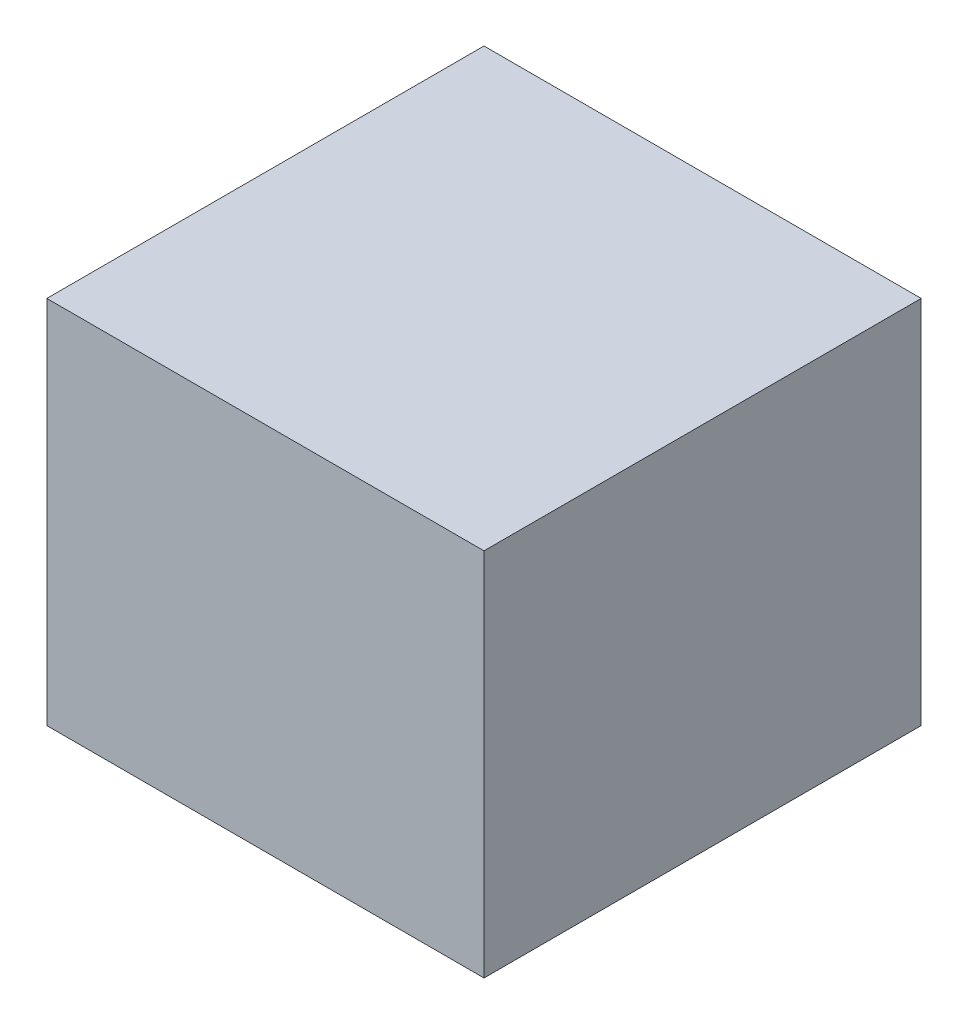
SolidWorks part; units mm, degrees
ref_plane "Front Plane" through (0, 0, 0) normal (0, 0, 1) x (1, 0, 0)
ref_plane "Top Plane" through (0, 0, 0) normal (0, 1, 0) x (1, 0, 0)
ref_plane "Right Plane" through (0, 0, 0) normal (1, 0, 0) x (0, 0, -1)
sketch "Sketch1" plane through (0, 0, 0) normal (0, 1, 0) x (1, 0, 0)
  line L1 (-165.1, -165.1) -> (165.1, -165.1)
  line L2 (-165.1, -165.1) -> (-165.1, 165.1)
  line L3 (-165.1, 165.1) -> (165.1, 165.1)
  line L4 (165.1, -165.1) -> (165.1, 165.1)
  line L5 (-165.1, -165.1) -> (165.1, 165.1) construction
  line L6 (-165.1, 165.1) -> (165.1, -165.1) construction
  point P0 (0, 0)
extrude "Boss-Extrude1" add sketch "Sketch1" along normal blind 279.4
